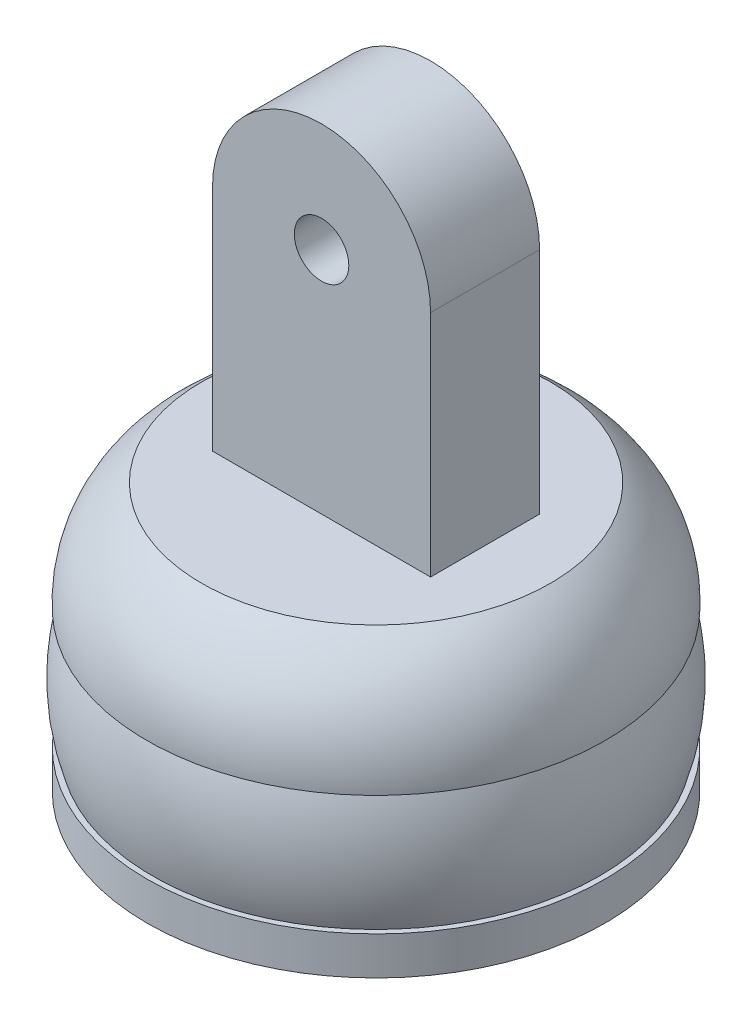
SolidWorks part; units mm, degrees
ref_plane "Front Plane" through (0, 0, 0) normal (0, 0, 1) x (1, 0, 0)
ref_plane "Top Plane" through (0, 0, 0) normal (0, 1, 0) x (1, 0, 0)
ref_plane "Right Plane" through (0, 0, 0) normal (1, 0, 0) x (0, 0, -1)
sketch "Sketch1" plane through (0, 0, 0) normal (0, 1, 0) x (1, 0, 0)
  circle A0 centre (0, 0) radius 21
  dimension "D1" = 42
extrude "Boss-Extrude1" add sketch "Sketch1" along normal blind 3.5
sketch "Sketch2" plane through (0, 0, 0) normal (0, 0, 1) x (1, 0, 0)
  line L0 (0, 3.5) -> (-20.5, 3.5)
  line L1 (21, 3.5) -> (-21, 3.5) construction
  line L2 (0, 3.5) -> (0, 14.5)
  line L3 (0, 14.5) -> (-20.5, 14.5)
  arc A2 (-20.5, 14.5) -> (-20.5, 3.5) centre (-3.3609, 9) ccw
  point P9 (-21.3609, 9)
  dimension "D3" = 18
  dimension "D4" = 18
  dimension "D1" = 20.5
  dimension "D2" = 11
revolve "Revolve3" add sketch "Sketch2" angle 360 about L2
sketch "Sketch4" plane through (0, 0, 0) normal (0, 0, 1) x (1, 0, 0)
  line L0 (0, 14.5) -> (21, 14.5)
  line L1 (20.5, 14.5) -> (-20.5, 14.5) construction
  line L2 (0, 14.5) -> (0, 24.5)
  line L3 (0, 24.5) -> (16, 24.5)
  arc A0 (16, 24.5) -> (21, 14.5) centre (9.5526, 15.0263) cw
revolve "Revolve4" add sketch "Sketch4" angle 360 about L2
sketch "Sketch5" plane through (0, 0, 0) normal (0, 0, 1) x (1, 0, 0)
  line L0 (0, 24.5) -> (10, 24.5)
  line L1 (16, 24.5) -> (-16, 24.5) construction
  line L2 (10, 24.5) -> (10, 45.5)
  line L4 (-10, 45.5) -> (-10, 24.5)
  line L5 (-10, 24.5) -> (0, 24.5)
  arc A0 (10, 45.5) -> (-10, 45.5) centre (0, 45.5) ccw
  circle A1 centre (0, 45.5) radius 2.5
  dimension "D3" = 5
  dimension "D1" = 21
  dimension "D2" = 20
extrude "Boss-Extrude2" add sketch "Sketch5" along normal mid plane 10
sketch "Sketch6" plane through (0, 0, -5) normal (0, 0, -1) x (-1, 0, 0)
  circle A0 centre (0, 45.5) radius 5
  circle A1 centre (0, 45.5) radius 2.5 construction
  circle A2 centre (0, 45.5) radius 2.5
  dimension "D1" = 10
extrude "Boss-Extrude3" add sketch "Sketch6" along normal mid plane 5
sketch "Sketch7" plane through (0, 0, 0) normal (0, -1, 0) x (1, 0, 0)
  circle A0 centre (0, 0) radius 17.5
  dimension "D1" = 35
extrude "Boss-Extrude4" add sketch "Sketch7" along normal mid plane 1.5
sketch "Sketch8" plane through (0, -0.75, 0) normal (0, -1, 0) x (-1, 0, 0)
  circle A0 centre (0, 0) radius 5
  dimension "D1" = 10
extrude "Boss-Extrude5" add sketch "Sketch8" along normal mid plane 5
sketch "Sketch10" plane through (0, 0, 0) normal (0, -1, 0) x (1, 0, 0)
  line L0 (0, 0) -> (21, 0) construction
  circle A0 centre (0, 0) radius 21 construction
  circle A1 centre (19.1488, 0) radius 1.125
  circle A2 centre (19.1488, 0) radius 0.625
  dimension "D1" = 2.25
  dimension "D2" = 1.25
  dimension "D3" = 1.8512
extrude "Boss-Extrude12" add sketch "Sketch10" along normal blind 0.5
pattern_circular "CirPattern1" count 30 over 360 about axis through (0, 0, 0) along (0, 1, 0) of "Boss-Extrude12"
